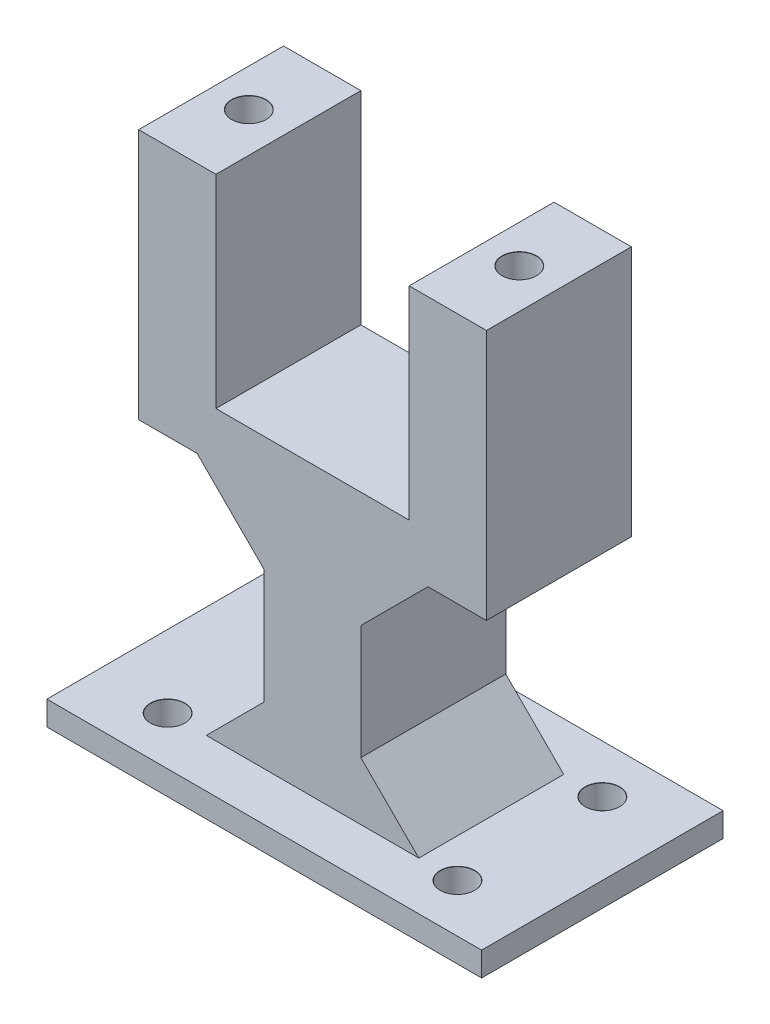
SolidWorks part; units mm, degrees
ref_plane "Front Plane" through (0, 0, 0) normal (0, 0, 1) x (1, 0, 0)
ref_plane "Top Plane" through (0, 0, 0) normal (0, 1, 0) x (1, 0, 0)
ref_plane "Right Plane" through (0, 0, 0) normal (1, 0, 0) x (0, 0, -1)
sketch "Sketch1" plane through (0, 0, 0) normal (0, 1, 0) x (1, 0, 0)
  line L0 (-28.575, 0) -> (28.575, 0) construction
  line L1 (-28.575, 15.875) -> (28.575, 15.875)
  line L2 (-28.575, 15.875) -> (-28.575, -15.875)
  line L3 (-28.575, -15.875) -> (28.575, -15.875)
  line L4 (28.575, 15.875) -> (28.575, -15.875)
  line L5 (0, -15.875) -> (0, 15.875) construction
  line L6 (-19.05, 9.525) -> (19.05, 9.525) construction
  line L7 (19.05, 9.525) -> (19.05, -9.525) construction
  point P8 (0, 0)
  point P10 (-19.05, 9.525)
  point P12 (19.05, 9.525)
  point P13 (-19.05, -9.525)
  point P14 (19.05, -9.525)
  point P15 (19.05, 0)
  point P16 (0, 9.525)
  dimension "D1" = 38.1
  dimension "D2" = 19.05
  dimension "D3" = 57.15
  dimension "D4" = 31.75
extrude "Boss-Extrude1" add sketch "Sketch1" along normal blind 3.175
hole_wizard "M4 Clearance Hole1" positions "Sketch4" profile "Sketch3" hole size "M4" standard "ANSI Metric" end condition through all
sketch "Sketch4" plane through (0, 3.175, 0) normal (0, 1, 0) x (1, 0, 0)
  point P0 (-19.05, 9.525)
  point P3 (19.05, 9.525)
  point P6 (19.05, -9.525)
  point P9 (-19.05, -9.525)
sketch "Sketch3" plane through (-19.05, 3.175, -9.525) normal (1, 0, 0) x (0, 0, 1)
  line L0 (0, 0) -> (0, 3.175)
  line L1 (0, 3.175) -> (2.25, 3.175)
  line L2 (2.25, 3.175) -> (2.25, 0.025)
  line L3 (2.25, 0.025) -> (2.275, 0)
  line L5 (2.275, 0) -> (0, 0)
  line L6 (-2.25, 0.025) -> (-2.275, 0) construction
  line L11 (0, -6.35) -> (0, 107.95) construction
  dimension "Thru Hole Dia." = 4.5
  dimension "Thru Hole Depth" = 3.175
  dimension "Near C'Sink Dia." = 4.55
  dimension "Near C'Sink Angle" = 90
sketch "Sketch5" plane through (0, 0, 0) normal (0, 0, 1) x (1, 0, 0)
  line L0 (-28.575, 3.175) -> (28.575, 3.175) construction
  line L1 (-6.35, 3.175) -> (6.35, 3.175)
  line L2 (-6.35, 3.175) -> (-6.35, 41.021)
  line L3 (-6.35, 41.021) -> (6.35, 41.021)
  line L4 (6.35, 3.175) -> (6.35, 41.021)
  point P6 (0, 3.175)
  dimension "D1" = 12.7
  dimension "D2" = 37.846
extrude "Boss-Extrude2" add sketch "Sketch5" along normal mid plane 19.05
sketch "Sketch6" plane through (0, 0, 0) normal (0, 0, 1) x (1, 0, 0)
  line L0 (6.35, 3.175) -> (6.35, 41.021) construction
  line L1 (6.35, 41.021) -> (12.7, 41.021)
  line L5 (0, 41.021) -> (0, 0) construction
  line L6 (6.35, 41.021) -> (-6.35, 41.021) construction
  line L7 (-28.575, 0) -> (28.575, 0) construction
  line L11 (-6.35, 41.021) -> (-12.7, 41.021)
  line L12 (-15.1751, 34.671) -> (-6.35, 25.8459)
  line L13 (-6.35, 41.021) -> (-6.35, 3.175) construction
  line L14 (15.1751, 34.671) -> (6.35, 25.8459)
  line L15 (-6.35, 25.8459) -> (-6.35, 41.021)
  line L16 (6.35, 41.021) -> (6.35, 25.8459)
  line L17 (-6.35, 10.795) -> (-13.97, 3.175)
  line L18 (-28.575, 3.175) -> (28.575, 3.175) construction
  line L19 (-13.97, 3.175) -> (-6.35, 3.175)
  line L20 (-6.35, 3.175) -> (-6.35, 10.795)
  line L21 (6.35, 3.175) -> (6.35, 10.795)
  line L22 (13.97, 3.175) -> (6.35, 3.175)
  line L23 (6.35, 10.795) -> (13.97, 3.175)
  line L24 (-12.7, 41.021) -> (-12.7, 67.691)
  line L25 (-12.7, 67.691) -> (-22.86, 67.691)
  line L26 (-22.86, 67.691) -> (-22.86, 34.671)
  line L27 (-22.86, 34.671) -> (-15.1751, 34.671)
  line L28 (22.86, 34.671) -> (15.1751, 34.671)
  line L29 (22.86, 67.691) -> (22.86, 34.671)
  line L30 (12.7, 67.691) -> (22.86, 67.691)
  line L31 (12.7, 41.021) -> (12.7, 67.691)
  dimension "D1" = 25.4
  dimension "D2" = 15.1751
  dimension "D3" = 45
  dimension "D4" = 45
  dimension "D5" = 7.62
  dimension "D6" = 10.16
  dimension "D7" = 26.67
  dimension "D8" = 6.35
extrude "Boss-Extrude3" add sketch "Sketch6" along normal mid plane 19.05
hole_wizard "M4 Clearance Hole2" positions "Sketch11" profile "Sketch8" hole size "M4" standard "ANSI Metric"
sketch "Sketch11" plane through (0, 67.691, 0) normal (0, 1, 0) x (1, 0, 0)
  line L0 (-28.575, 0) -> (28.575, 0) construction
  point P0 (-17.9032, 0)
  point P4 (17.6568, 0)
  dimension "D1" = 35.56
sketch "Sketch8" plane through (-17.9032, 67.691, 0) normal (1, 0, 0) x (0, 0, 1)
  line L0 (0, 0) -> (0, 34.3719)
  line L1 (0, 34.3719) -> (2.25, 33.02)
  line L2 (2.25, 33.02) -> (2.25, 0.025)
  line L3 (2.25, 0.025) -> (2.275, 0)
  line L5 (2.275, 0) -> (0, 0)
  line L6 (-2.25, 0.025) -> (-2.275, 0) construction
  line L10 (0, 34.3719) -> (-2.25, 33.02) construction
  line L11 (0, -6.35) -> (0, 107.95) construction
  dimension "Hole Dia." = 4.5
  dimension "Hole Depth" = 33.02
  dimension "Near C'Sink Dia." = 4.55
  dimension "Near C'Sink Angle" = 90
  dimension "Drill Angle" = 118
